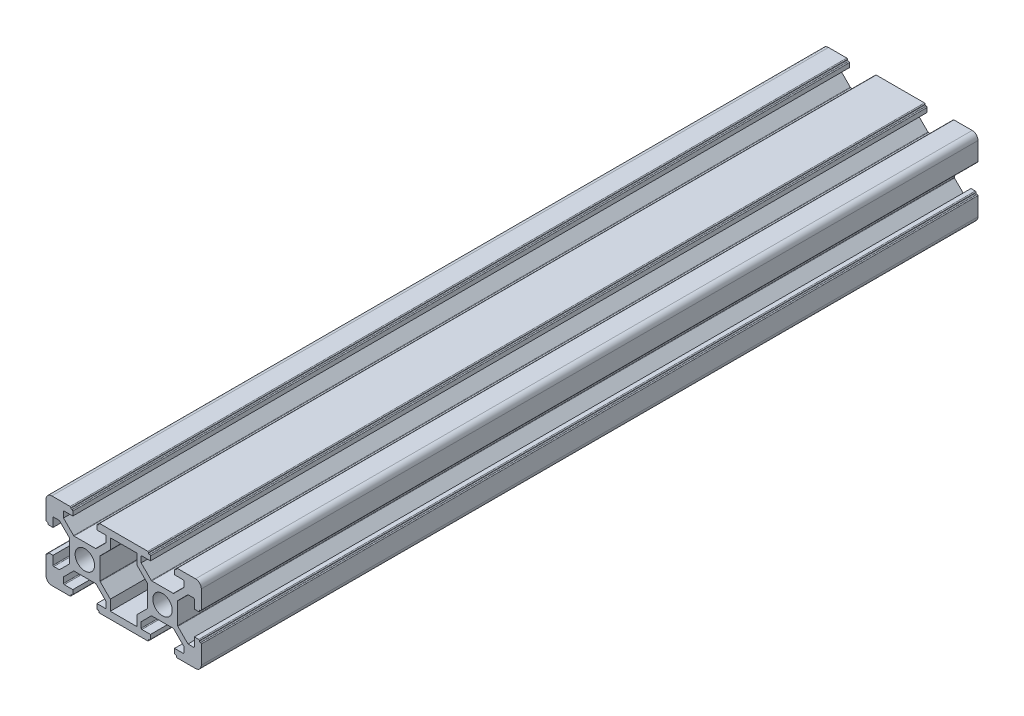
SolidWorks part; units mm, degrees
ref_plane "前视基准面" through (0, 0, 0) normal (0, 0, 1) x (1, 0, 0)
ref_plane "上视基准面" through (0, 0, 0) normal (0, 1, 0) x (1, 0, 0)
ref_plane "右视基准面" through (0, 0, 0) normal (1, 0, 0) x (0, 0, -1)
sketch "Sketch1" plane through (0, 0, 0) normal (0, 0, 1) x (1, 0, 0)
  line L0 (-8.5, 10) -> (-3.8, 10)
  line L3 (-8.5, -10) -> (-3.8, -10)
  line L5 (-10, 8.5) -> (-10, 3.8)
  line L6 (-2.7565, 3.9) -> (2.7565, 3.9)
  line L9 (-2.7565, -3.9) -> (2.7565, -3.9)
  line L10 (3.9, 2.7565) -> (3.9, -2.7565)
  line L11 (-3.9, 2.7565) -> (-3.9, -2.7565)
  line L12 (-3.9586, -2.8979) -> (-6.5607, -5.5)
  line L13 (3.6, 9.7) -> (3.6, 9.8)
  line L14 (3.1, -8.2) -> (5.3, -8.2)
  line L15 (-2.8979, -3.9586) -> (-5.5, -6.5607)
  line L16 (-3.1, -8.2) -> (-3.1, -9.3)
  line L17 (3.1, -8.2) -> (3.1, -9.3)
  line L18 (-5.5, -6.5607) -> (-5.5, -8)
  line L19 (5.5, -6.5607) -> (5.5, -8)
  line L20 (-5.3, -8.2) -> (-3.1, -8.2)
  line L21 (-3.4, -9.5) -> (-3.3, -9.5)
  line L22 (3.8, -10) -> (8.5, -10)
  line L23 (3.3, -9.5) -> (3.4, -9.5)
  line L24 (-3.6, -9.7) -> (-3.6, -9.8)
  line L25 (3.6, -9.7) -> (3.6, -9.8)
  line L26 (-6.5607, -5.5) -> (-8, -5.5)
  line L27 (-9.7, -3.6) -> (-9.8, -3.6)
  line L28 (-9.5, -3.4) -> (-9.5, -3.3)
  line L29 (-8.2, -3.1) -> (-9.3, -3.1)
  line L30 (-8.2, -5.3) -> (-8.2, -3.1)
  line L31 (-10, -3.8) -> (-10, -8.5)
  line L33 (3.8, 10) -> (8.5, 10)
  line L34 (2.8979, -3.9586) -> (5.5, -6.5607)
  line L40 (3.9586, -2.8979) -> (6.5607, -5.5)
  line L41 (3.3, 9.5) -> (3.4, 9.5)
  line L42 (30, 8.5) -> (30, 3.8)
  line L43 (3.1, 8.2) -> (3.1, 9.3)
  line L44 (3.1, 8.2) -> (5.3, 8.2)
  line L45 (5.5, 6.5607) -> (5.5, 8)
  line L46 (2.8979, 3.9586) -> (5.5, 6.5607)
  line L52 (3.9586, 2.8979) -> (6.5607, 5.5)
  line L53 (-3.6, 9.7) -> (-3.6, 9.8)
  line L54 (-3.4, 9.5) -> (-3.3, 9.5)
  line L55 (-3.1, 8.2) -> (-3.1, 9.3)
  line L56 (-5.3, 8.2) -> (-3.1, 8.2)
  line L57 (-5.5, 6.5607) -> (-5.5, 8)
  line L58 (-2.8979, 3.9586) -> (-5.5, 6.5607)
  line L59 (-9.5, 3.4) -> (-9.5, 3.3)
  line L60 (-9.7, 3.6) -> (-9.8, 3.6)
  line L61 (-8.2, 3.1) -> (-9.3, 3.1)
  line L62 (-8.2, 5.3) -> (-8.2, 3.1)
  line L63 (-6.5607, 5.5) -> (-8, 5.5)
  line L64 (-3.9586, 2.8979) -> (-6.5607, 5.5)
  line L65 (29.7, 3.6) -> (29.8, 3.6)
  line L66 (29.5, 3.4) -> (29.5, 3.3)
  line L67 (28.2, 3.1) -> (29.3, 3.1)
  line L68 (28.2, 5.3) -> (28.2, 3.1)
  line L69 (26.5607, 5.5) -> (28, 5.5)
  line L70 (23.9586, 2.8979) -> (26.5607, 5.5)
  line L71 (23.9, 2.7565) -> (23.9, -2.7565)
  line L72 (23.9586, -2.8979) -> (26.5607, -5.5)
  line L73 (26.5607, -5.5) -> (28, -5.5)
  line L74 (28.2, -5.3) -> (28.2, -3.1)
  line L75 (28.2, -3.1) -> (29.3, -3.1)
  line L76 (29.5, -3.4) -> (29.5, -3.3)
  line L77 (29.7, -3.6) -> (29.8, -3.6)
  line L78 (30, -3.8) -> (30, -8.5)
  line L79 (28.5, -10) -> (23.8, -10)
  line L80 (23.6, -9.7) -> (23.6, -9.8)
  line L81 (23.4, -9.5) -> (23.3, -9.5)
  line L82 (23.1, -8.2) -> (23.1, -9.3)
  line L83 (25.3, -8.2) -> (23.1, -8.2)
  line L84 (25.5, -6.5607) -> (25.5, -8)
  line L85 (22.8979, -3.9586) -> (25.5, -6.5607)
  line L86 (22.7565, -3.9) -> (17.2435, -3.9)
  line L87 (17.1021, -3.9586) -> (14.5, -6.5607)
  line L88 (14.5, -6.5607) -> (14.5, -8)
  line L89 (16.9, -8.2) -> (14.7, -8.2)
  line L90 (16.9, -8.2) -> (16.9, -9.3)
  line L91 (16.7, -9.5) -> (16.6, -9.5)
  line L92 (16.4, -9.7) -> (16.4, -9.8)
  line L93 (16.2, -10) -> (11.5, -10)
  line L94 (13.4393, 5.5) -> (13.4393, 8.2)
  line L96 (6.5607, 5.5) -> (6.5607, 8.2)
  line L97 (6.5607, 8.2) -> (13.4393, 8.2)
  line L99 (16.0414, -2.8979) -> (13.4393, -5.5)
  line L100 (16.1, 2.7565) -> (16.1, -2.7565)
  line L101 (16.0414, 2.8979) -> (13.4393, 5.5)
  line L107 (16.2, 10) -> (11.5, 10)
  line L108 (16.4, 9.7) -> (16.4, 9.8)
  line L109 (16.7, 9.5) -> (16.6, 9.5)
  line L110 (16.9, 8.2) -> (16.9, 9.3)
  line L111 (16.9, 8.2) -> (14.7, 8.2)
  line L112 (14.5, 6.5607) -> (14.5, 8)
  line L113 (17.1021, 3.9586) -> (14.5, 6.5607)
  line L114 (22.7565, 3.9) -> (17.2435, 3.9)
  line L115 (22.8979, 3.9586) -> (25.5, 6.5607)
  line L116 (25.5, 6.5607) -> (25.5, 8)
  line L117 (25.3, 8.2) -> (23.1, 8.2)
  line L118 (23.1, 8.2) -> (23.1, 9.3)
  line L119 (23.4, 9.5) -> (23.3, 9.5)
  line L120 (23.6, 9.7) -> (23.6, 9.8)
  line L121 (28.5, 10) -> (23.8, 10)
  line L122 (13.4393, -5.5) -> (13.4393, -8.2)
  line L124 (6.5607, -5.5) -> (6.5607, -8.2)
  line L125 (6.5607, -8.2) -> (13.4393, -8.2)
  line L127 (8.5, 10) -> (11.5, 10)
  line L128 (8.5, -10) -> (11.5, -10)
  arc A3 (-8.5, -10) -> (-10, -8.5) centre (-8.5, -8.5) cw
  arc A4 (-10, 8.5) -> (-8.5, 10) centre (-8.5, 8.5) cw
  arc A5 (3.4, -9.5) -> (3.6, -9.7) centre (3.4, -9.7) cw
  arc A6 (3.8, -10) -> (3.6, -9.8) centre (3.8, -9.8) cw
  arc A7 (3.3, -9.5) -> (3.1, -9.3) centre (3.3, -9.3) cw
  arc A8 (5.3, -8.2) -> (5.5, -8) centre (5.3, -8) ccw
  arc A9 (-3.9, -2.7565) -> (-3.9586, -2.8979) centre (-4.1, -2.7565) cw
  arc A10 (-3.9, 2.7565) -> (-3.9586, 2.8979) centre (-4.1, 2.7565) ccw
  arc A11 (-2.7565, 3.9) -> (-2.8979, 3.9586) centre (-2.7565, 4.1) cw
  arc A12 (2.7565, 3.9) -> (2.8979, 3.9586) centre (2.7565, 4.1) ccw
  arc A13 (3.9586, 2.8979) -> (3.9, 2.7565) centre (4.1, 2.7565) ccw
  arc A14 (3.9, -2.7565) -> (3.9586, -2.8979) centre (4.1, -2.7565) ccw
  arc A15 (-2.8979, -3.9586) -> (-2.7565, -3.9) centre (-2.7565, -4.1) cw
  arc A16 (2.7565, -3.9) -> (2.8979, -3.9586) centre (2.7565, -4.1) cw
  arc A17 (-3.6, -9.8) -> (-3.8, -10) centre (-3.8, -9.8) cw
  arc A18 (-3.3, -9.5) -> (-3.1, -9.3) centre (-3.3, -9.3) ccw
  arc A19 (-3.6, -9.7) -> (-3.4, -9.5) centre (-3.4, -9.7) cw
  arc A20 (-8.2, 5.3) -> (-8, 5.5) centre (-8, 5.3) cw
  arc A23 (-8.2, -5.3) -> (-8, -5.5) centre (-8, -5.3) ccw
  arc A24 (-5.3, -8.2) -> (-5.5, -8) centre (-5.3, -8) cw
  arc A31 (3.1, 9.3) -> (3.3, 9.5) centre (3.3, 9.3) cw
  arc A32 (3.6, 9.8) -> (3.8, 10) centre (3.8, 9.8) cw
  arc A33 (3.6, 9.7) -> (3.4, 9.5) centre (3.4, 9.7) cw
  arc A34 (-3.8, 10) -> (-3.6, 9.8) centre (-3.8, 9.8) cw
  arc A35 (-3.3, 9.5) -> (-3.1, 9.3) centre (-3.3, 9.3) cw
  arc A36 (-3.4, 9.5) -> (-3.6, 9.7) centre (-3.4, 9.7) cw
  arc A37 (5.5, 8) -> (5.3, 8.2) centre (5.3, 8) ccw
  arc A38 (-5.5, 8) -> (-5.3, 8.2) centre (-5.3, 8) cw
  arc A39 (-10, 3.8) -> (-9.8, 3.6) centre (-9.8, 3.8) ccw
  arc A40 (-9.5, 3.3) -> (-9.3, 3.1) centre (-9.3, 3.3) ccw
  arc A41 (-9.7, 3.6) -> (-9.5, 3.4) centre (-9.7, 3.4) cw
  arc A42 (-10, -3.8) -> (-9.8, -3.6) centre (-9.8, -3.8) cw
  arc A43 (-9.5, -3.3) -> (-9.3, -3.1) centre (-9.3, -3.3) cw
  arc A44 (-9.5, -3.4) -> (-9.7, -3.6) centre (-9.7, -3.4) cw
  arc A45 (30, 8.5) -> (28.5, 10) centre (28.5, 8.5) ccw
  arc A46 (30, 3.8) -> (29.8, 3.6) centre (29.8, 3.8) cw
  arc A47 (29.7, 3.6) -> (29.5, 3.4) centre (29.7, 3.4) ccw
  arc A48 (29.5, 3.3) -> (29.3, 3.1) centre (29.3, 3.3) cw
  arc A49 (28.2, 5.3) -> (28, 5.5) centre (28, 5.3) ccw
  arc A50 (23.9, 2.7565) -> (23.9586, 2.8979) centre (24.1, 2.7565) cw
  arc A51 (23.9, -2.7565) -> (23.9586, -2.8979) centre (24.1, -2.7565) ccw
  arc A52 (28.2, -5.3) -> (28, -5.5) centre (28, -5.3) cw
  arc A53 (29.5, -3.3) -> (29.3, -3.1) centre (29.3, -3.3) ccw
  arc A54 (29.5, -3.4) -> (29.7, -3.6) centre (29.7, -3.4) ccw
  arc A55 (30, -3.8) -> (29.8, -3.6) centre (29.8, -3.8) ccw
  arc A56 (28.5, -10) -> (30, -8.5) centre (28.5, -8.5) ccw
  arc A57 (23.6, -9.8) -> (23.8, -10) centre (23.8, -9.8) ccw
  arc A58 (23.6, -9.7) -> (23.4, -9.5) centre (23.4, -9.7) ccw
  arc A59 (23.3, -9.5) -> (23.1, -9.3) centre (23.3, -9.3) cw
  arc A60 (25.3, -8.2) -> (25.5, -8) centre (25.3, -8) ccw
  arc A61 (22.8979, -3.9586) -> (22.7565, -3.9) centre (22.7565, -4.1) ccw
  arc A62 (17.2435, -3.9) -> (17.1021, -3.9586) centre (17.2435, -4.1) ccw
  arc A63 (14.7, -8.2) -> (14.5, -8) centre (14.7, -8) cw
  arc A64 (16.7, -9.5) -> (16.9, -9.3) centre (16.7, -9.3) ccw
  arc A65 (16.6, -9.5) -> (16.4, -9.7) centre (16.6, -9.7) ccw
  arc A66 (16.2, -10) -> (16.4, -9.8) centre (16.2, -9.8) ccw
  arc A72 (16.1, -2.7565) -> (16.0414, -2.8979) centre (15.9, -2.7565) cw
  arc A73 (16.0414, 2.8979) -> (16.1, 2.7565) centre (15.9, 2.7565) cw
  arc A79 (16.4, 9.8) -> (16.2, 10) centre (16.2, 9.8) ccw
  arc A80 (16.4, 9.7) -> (16.6, 9.5) centre (16.6, 9.7) ccw
  arc A81 (16.9, 9.3) -> (16.7, 9.5) centre (16.7, 9.3) ccw
  arc A82 (14.5, 8) -> (14.7, 8.2) centre (14.7, 8) cw
  arc A83 (17.2435, 3.9) -> (17.1021, 3.9586) centre (17.2435, 4.1) cw
  arc A84 (22.7565, 3.9) -> (22.8979, 3.9586) centre (22.7565, 4.1) ccw
  arc A85 (25.5, 8) -> (25.3, 8.2) centre (25.3, 8) ccw
  arc A86 (23.3, 9.5) -> (23.1, 9.3) centre (23.3, 9.3) ccw
  arc A87 (23.4, 9.5) -> (23.6, 9.7) centre (23.4, 9.7) ccw
  arc A88 (23.8, 10) -> (23.6, 9.8) centre (23.8, 9.8) ccw
  point P11 (3.9, 3.9)
  point P19 (3.3697, 4.4303)
  point P20 (-10.6428, -10.6428)
  point P25 (-11.1731, -10.1124)
  point P26 (4.4303, 3.3697)
  point P28 (-10.1124, -11.1731)
  dimension "D3" = 0.2
  dimension "D4" = 0.2
  dimension "D5" = 0.2
  dimension "D8" = 0.2
  dimension "D9" = 0.2
  dimension "D10" = 0.2
  dimension "D6" = 1.8
  dimension "D7" = 0.5
extrude "Boss-Extrude1" add sketch "Sketch1" along normal blind 200
ref_plane "hole" through (0, 0, 200) normal (0, 0, 1) x (1, 0, 0)
sketch "Sketch2" plane through (0, 0, 200) normal (0, 0, 1) x (1, 0, 0)
  circle A0 centre (0, 0) radius 2.5
  circle A1 centre (20, 0) radius 2.5
  dimension "D1" = 5
extrude "Cut-Extrude1" cut sketch "Sketch2" against normal through all
sketch "Sketch3" plane through (0, -3.9, 0) normal (0, -1, 0) x (1, 0, 0)
  line L0 (17.2435, 200) -> (22.7565, 200) construction
  line L1 (20, 200) -> (0, 200) construction
  line L2 (-2.7565, 200) -> (2.7565, 200) construction
  line L3 (10, 200) -> (10, 151.4468) construction
  circle A0 centre (20, 183.3) radius 1.5
  circle A1 centre (20, 166.6) radius 1.5
  circle A2 centre (0, 166.6) radius 1.5
  circle A3 centre (0, 183.3) radius 1.5
  point P6 (20, 200)
  dimension "D1" = 0
  dimension "D2" = 0
  dimension "D3" = 16.7
  dimension "D4" = 16.7
  dimension "D5" = 3
  dimension "D6" = 3
extrude "Cut-Extrude2" cut sketch "Sketch3" against normal blind 10
